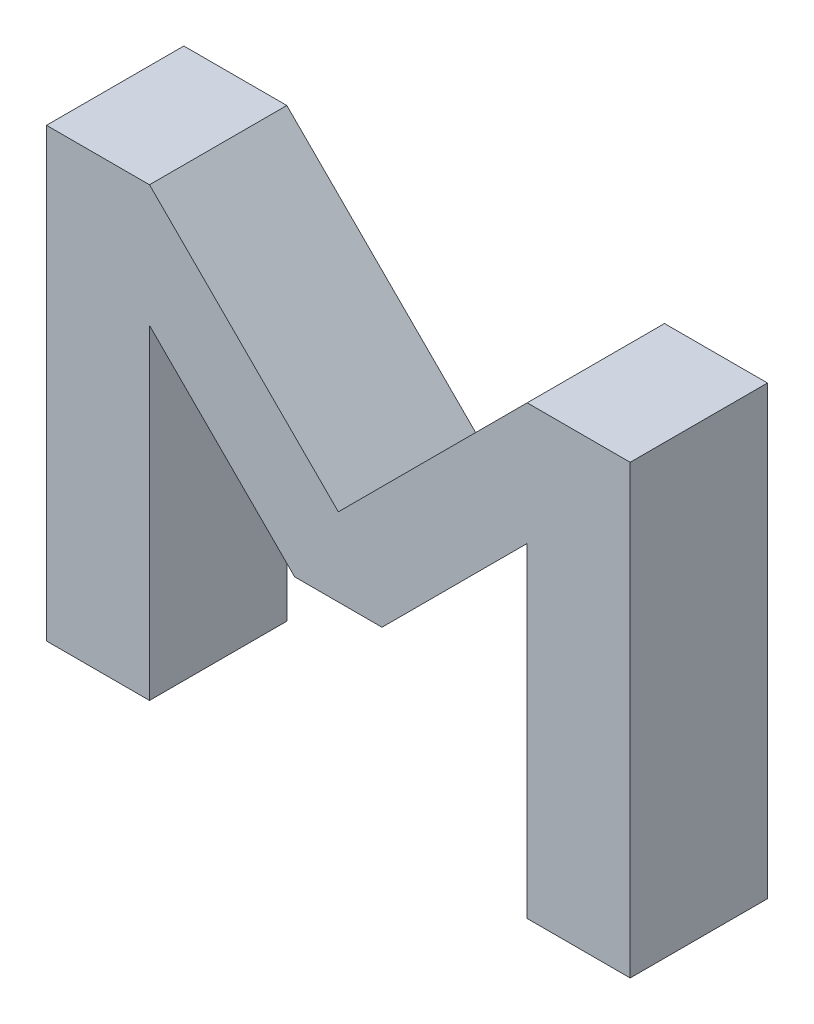
SolidWorks part; units mm, degrees
ref_plane "Front Plane" through (0, 0, 0) normal (0, 0, 1) x (1, 0, 0)
ref_plane "Top Plane" through (0, 0, 0) normal (0, 1, 0) x (1, 0, 0)
ref_plane "Right Plane" through (0, 0, 0) normal (1, 0, 0) x (0, 0, -1)
sketch "Sketch1" plane through (0, 0, 0) normal (0, 0, 1) x (1, 0, 0)
  line L64 (175.0781, 68.1821) -> (175.0781, 133.2285)
  line L65 (175.0781, 133.2285) -> (190.0781, 133.2285)
  line L66 (175.0781, 68.1821) -> (190.0781, 68.1821)
  line L67 (190.0781, 68.1821) -> (190.0781, 115.4886)
  line L68 (190.0781, 115.4886) -> (211.2207, 94.346)
  line L69 (211.2207, 94.346) -> (223.9393, 94.346)
  line L70 (190.0781, 133.2285) -> (217.58, 105.7266)
  line L72 (245.0818, 133.2285) -> (217.58, 105.7266)
  line L73 (245.0818, 115.4886) -> (223.9393, 94.346)
  line L74 (245.0818, 68.1821) -> (245.0818, 115.4886)
  line L75 (260.0818, 68.1821) -> (245.0818, 68.1821)
  line L76 (260.0818, 133.2285) -> (245.0818, 133.2285)
  line L77 (260.0818, 68.1821) -> (260.0818, 133.2285)
  point P76 (217.58, 94.346)
extrude "Boss-Extrude1" add sketch "Sketch1" along normal blind 20 contours L70 L72 L76 L77 L75 L74 L73 L69 L68 L67 L66 L64 L65
